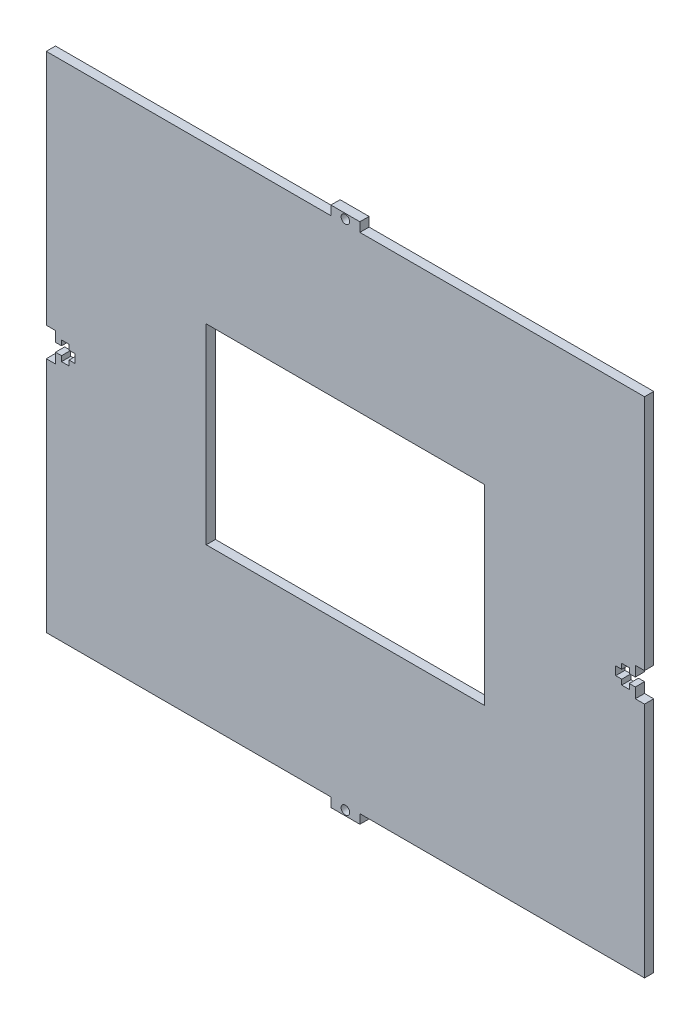
SolidWorks part; units mm, degrees
ref_plane "Front Plane" through (0, 0, 0) normal (0, 0, 1) x (1, 0, 0)
ref_plane "Top Plane" through (0, 0, 0) normal (0, 1, 0) x (1, 0, 0)
ref_plane "Right Plane" through (0, 0, 0) normal (1, 0, 0) x (0, 0, -1)
sketch "Sketch2" plane through (0, 0, 0) normal (0, 0, 1) x (1, 0, 0)
  line L1 (-103.18, -86.82) -> (103.18, -86.82)
  line L2 (-103.18, -86.82) -> (-103.18, 86.82)
  line L3 (-103.18, 86.82) -> (103.18, 86.82)
  line L4 (103.18, -86.82) -> (103.18, 86.82)
  line L5 (-103.18, -86.82) -> (103.18, 86.82) construction
  line L6 (-103.18, 86.82) -> (103.18, -86.82) construction
  point P0 (0, 0)
  dimension "D1" = 173.64
  dimension "D2" = 206.36
extrude "Boss-Extrude1" add sketch "Sketch2" along normal blind 3.18
sketch "Sketch3" plane through (0, 0, 3.18) normal (0, 0, 1) x (1, 0, 0)
  line L0 (103.18, 86.82) -> (-103.18, 86.82) construction
  line L5 (0, 86.82) -> (0, 25.4128) construction
  line L19 (-103.18, 0) -> (103.18, 0) construction
  line L20 (-103.18, 86.82) -> (-103.18, -86.82) construction
  line L21 (103.18, -86.82) -> (103.18, 86.82) construction
  line L38 (-95.32, -1.47) -> (-95.32, -3.25)
  line L39 (-103.18, 5) -> (-100, 5)
  line L40 (-103.18, 5) -> (-103.18, -5)
  line L41 (-103.18, -5) -> (-100, -5)
  line L42 (-100, 5) -> (-100, 1.47)
  line L43 (-100, -1.47) -> (-97.92, -1.47)
  line L45 (-100, 1.47) -> (-97.92, 1.47)
  line L46 (-93.25, -1.47) -> (-93.25, 1.47)
  line L47 (-97.92, 3.25) -> (-95.32, 3.25)
  line L48 (-97.92, 3.25) -> (-97.92, 1.47)
  line L49 (-97.92, -3.25) -> (-95.32, -3.25)
  line L50 (-95.32, 3.25) -> (-95.32, 1.47)
  line L51 (-95.32, -1.47) -> (-93.25, -1.47)
  line L52 (-97.92, -1.47) -> (-97.92, -3.25)
  line L53 (-100, -1.47) -> (-100, -5)
  line L54 (-95.32, 1.47) -> (-93.25, 1.47)
  point P55 (-96.62, 3.25)
  dimension "D8" = 10
  dimension "D9" = 2.6
  dimension "D10" = 6.5
  dimension "D11" = 3.18
  dimension "D12" = 2.94
  dimension "D13" = 2.08
  dimension "D14" = 6.75
extrude "Cut-Extrude1" cut sketch "Sketch3" against normal through all
sketch "Sketch9" plane through (0, 86.82, 0) normal (0, 1, 0) x (1, 0, 0)
  line L0 (0, 0) -> (0, -11.7583) construction
  line L1 (103.18, 0) -> (-103.18, 0) construction
  line L2 (-5, 0) -> (5, 0)
  line L3 (-5, 0) -> (-5, -3.18)
  line L4 (-5, -3.18) -> (5, -3.18)
  line L5 (5, 0) -> (5, -3.18)
  line L6 (103.18, -3.18) -> (-103.18, -3.18) construction
  dimension "D1" = 10
extrude "Boss-Extrude4" add sketch "Sketch9" along normal blind 3.18
sketch "Sketch11" plane through (0, 0, 3.18) normal (0, 0, 1) x (1, 0, 0)
  line L0 (0, 0) -> (0, 84.6375) construction
  line L1 (-5, 90) -> (5, 90) construction
  circle A0 centre (0, 88.25) radius 1.47
  dimension "D1" = 2.94
  dimension "D2" = 1.75
extrude "Cut-Extrude3" cut sketch "Sketch11" against normal through all
mirror "Mirror1" about plane through (0, 0, 0) normal (1, 0, 0) of "Cut-Extrude1"
mirror "Mirror2" about plane through (0, 0, 0) normal (0, 1, 0) of "Cut-Extrude3", "Boss-Extrude4"
sketch "Sketch12" plane through (0, 0, 3.18) normal (0, 0, 1) x (1, 0, 0)
  line L1 (48, 33) -> (-48, 33)
  line L2 (48, 33) -> (48, -33)
  line L3 (48, -33) -> (-48, -33)
  line L4 (-48, 33) -> (-48, -33)
  line L5 (48, 33) -> (-48, -33) construction
  line L6 (48, -33) -> (-48, 33) construction
  point P0 (0, 0)
  dimension "D1" = 96
  dimension "D2" = 66
extrude "Cut-Extrude4" cut sketch "Sketch12" against normal through all
